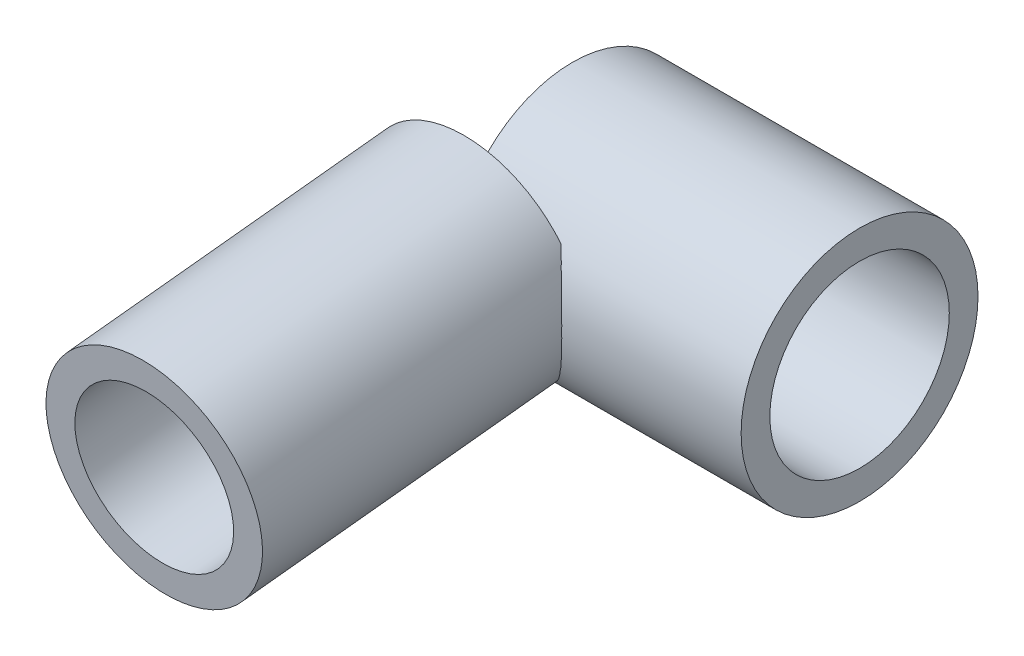
SolidWorks part; units mm, degrees
ref_plane "Front Plane" through (0, 0, 0) normal (0, 0, 1) x (1, 0, 0)
ref_plane "Plane_top" through (0, 0, 0) normal (0, 1, 0) x (1, 0, 0)
ref_plane "Right Plane" through (0, 0, 0) normal (1, 0, 0) x (0, 0, -1)
sketch "Sketch1" plane through (0, 0, 0) normal (0, 1, 0) x (1, 0, 0)
  line L0 (-470.9414, 0) -> (529.0586, 0) construction
  dimension "D1" = 1000
ref_plane "Plane_lower" through (0, -100, 0) normal (0, 1, 0) x (1, 0, 0)
sketch "Sketch2" plane through (0, -100, 0) normal (0, 1, 0) x (1, 0, 0)
  line L0 (0, 0) -> (0, -940) construction
  line L1 (0, -940) -> (25, -940) construction
  dimension "D1" = 940
  dimension "D2" = 25
ref_plane "Real_plane" through (0, 0, 0) normal (0, 0.9944, 0.1058) x (1, 0, 0)
sketch "Sketch4" plane through (0, 0, 0) normal (0, 0.9944, 0.1058) x (1, 0, 0)
  line L0 (0, 0) -> (0, -40) construction
  line L1 (15, 3) -> (15, -42)
  line L2 (11, 3) -> (11, -42)
  line L3 (11, 3) -> (15, 3)
  line L4 (11, -42) -> (15, -42)
  dimension "D1" = 40
  dimension "D2" = 11
  dimension "D3" = 15
  dimension "D4" = 45
  dimension "D5" = 3
revolve "Revolve1" add sketch "Sketch4" angle 360 about L0
sketch "Sketch5" plane through (0, 0, 0) normal (0, 1, 0) x (1, 0, 0)
  line L0 (0, 0) -> (0, 16.5) construction
  line L1 (0, 16.5) -> (69.3947, 16.5) construction
  line L4 (40, 4) -> (0, 4)
  line L5 (40, 0) -> (0, 0)
  line L6 (0, 0) -> (0, 4)
  line L7 (40, 0) -> (40, 4)
  point P0 (0, 0)
  point P3 (0, 17)
  point P9 (0, 34)
  point P10 (0, 0)
  dimension "D1" = 16.5
  dimension "D2" = 4
  dimension "D3" = 40
revolve "Revolve2" add sketch "Sketch5" angle 360 about L1
